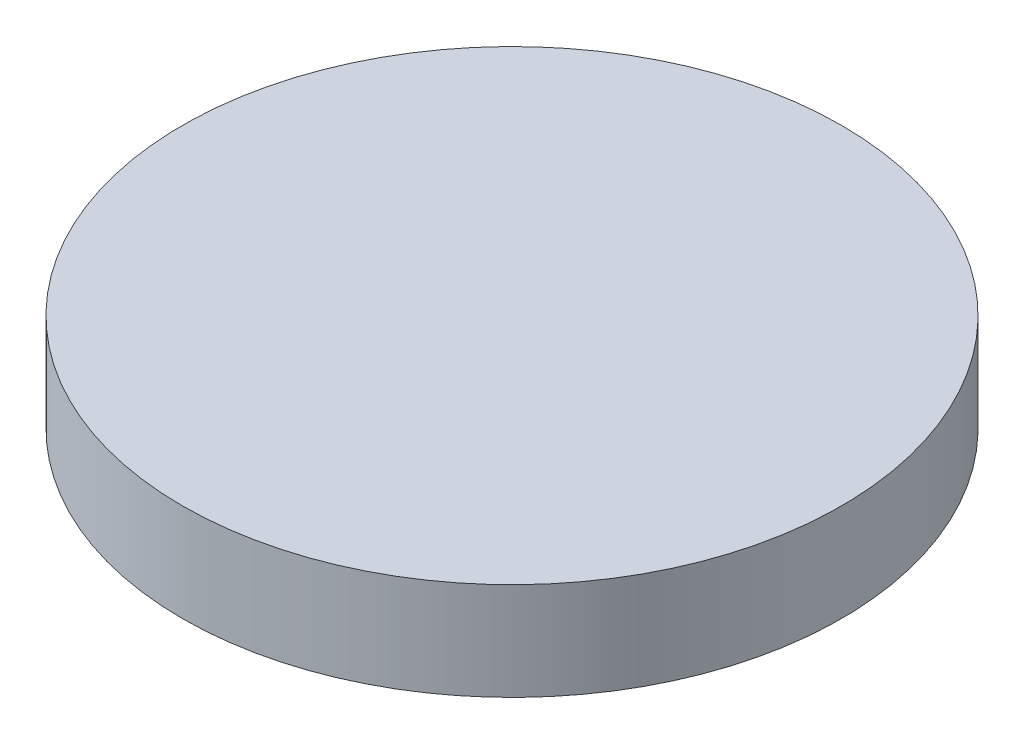
SolidWorks part; units mm, degrees
ref_plane "Front Plane" through (0, 0, 0) normal (0, 0, 1) x (1, 0, 0)
ref_plane "Top Plane" through (0, 0, 0) normal (0, 1, 0) x (1, 0, 0)
ref_plane "Right Plane" through (0, 0, 0) normal (1, 0, 0) x (0, 0, -1)
sketch "Sketch1" plane through (0, 0, 0) normal (0, 1, 0) x (1, 0, 0)
  circle A0 centre (0, 0) radius 34.29
  dimension "D1" = 68.58
extrude "Boss-Extrude1" add sketch "Sketch1" along normal blind 10.16
